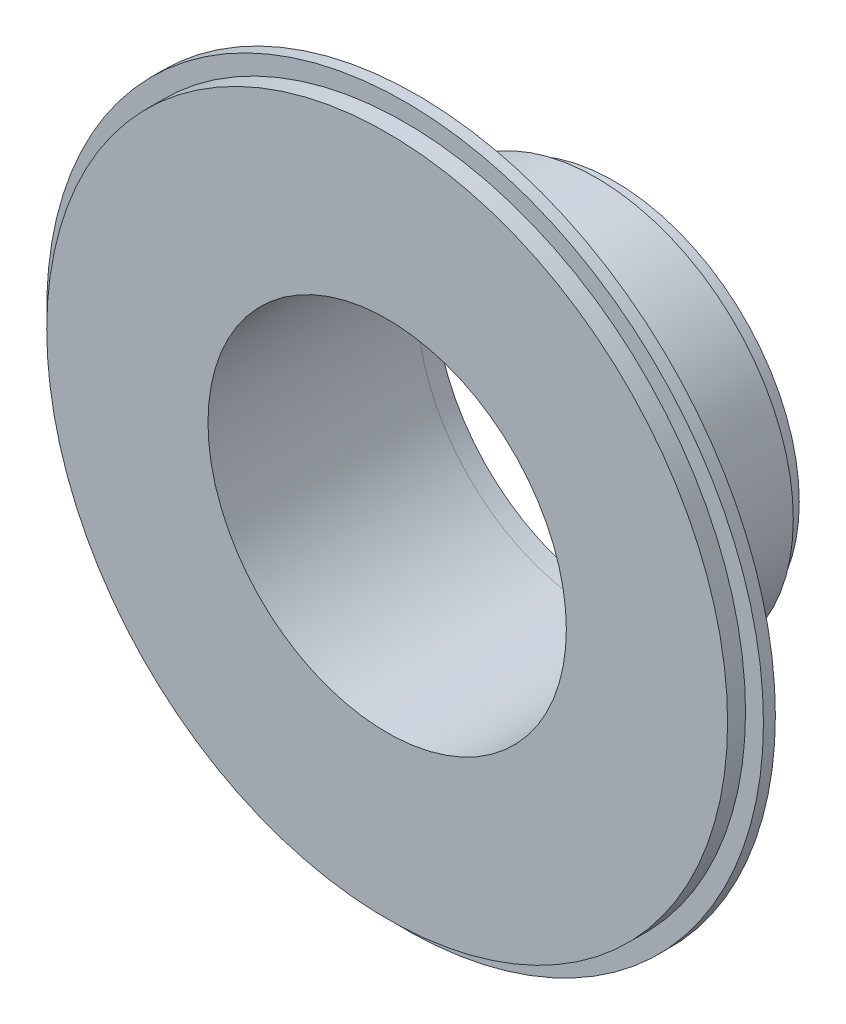
SolidWorks part; units mm, degrees
ref_plane "정면" through (0, 0, 0) normal (0, 0, 1) x (1, 0, 0)
ref_plane "윗면" through (0, 0, 0) normal (0, 1, 0) x (1, 0, 0)
ref_plane "우측면" through (0, 0, 0) normal (1, 0, 0) x (0, 0, -1)
sketch "스케치1" plane through (0, 0, 0) normal (0, 0, 1) x (1, 0, 0)
  circle A0 centre (0, 0) radius 30
  circle A1 centre (0, 0) radius 31
  dimension "D1" = 62
  dimension "D2" = 60
extrude "보스-돌출1" add sketch "스케치1" against normal blind 3
sketch "스케치2" plane through (0, 0, 0) normal (0, 0, 1) x (1, 0, 0)
  circle A0 centre (0, 0) radius 33
  circle A1 centre (0, 0) radius 31 construction
  circle A2 centre (0, 0) radius 31
  circle A3 centre (0, 0) radius 30 construction
  circle A4 centre (0, 0) radius 30
  circle M1 centre (0, 0) radius 30
  circle M2 centre (0, 0) radius 31
  dimension "D1" = 66
extrude "보스-돌출3" add sketch "스케치2" along normal blind 30 separate body contours A0 M2 | M2 M1 | A2
sketch "스케치4" plane through (0, 0, 30) normal (0, 0, 1) x (1, 0, 0)
  circle A0 centre (0, 0) radius 60
  circle A1 centre (0, 0) radius 33 construction
  circle A2 centre (0, 0) radius 33
  circle A3 centre (0, 0) radius 30 construction
  circle A4 centre (0, 0) radius 30
  circle M2 centre (0, 0) radius 33
  circle M3 centre (0, 0) radius 30
  dimension "D1" = 120
extrude "보스-돌출4" add sketch "스케치4" along normal blind 5 contours M2 M3 | A0 M2
sketch "스케치5" plane through (0, 0, 35) normal (0, 0, 1) x (1, 0, 0)
  circle A0 centre (0, 0) radius 60 construction
  circle A1 centre (0, 0) radius 60
  circle A2 centre (0, 0) radius 57
  dimension "D1" = 3
extrude "컷-돌출1" cut sketch "스케치5" against normal blind 3 contours A1 | A2
